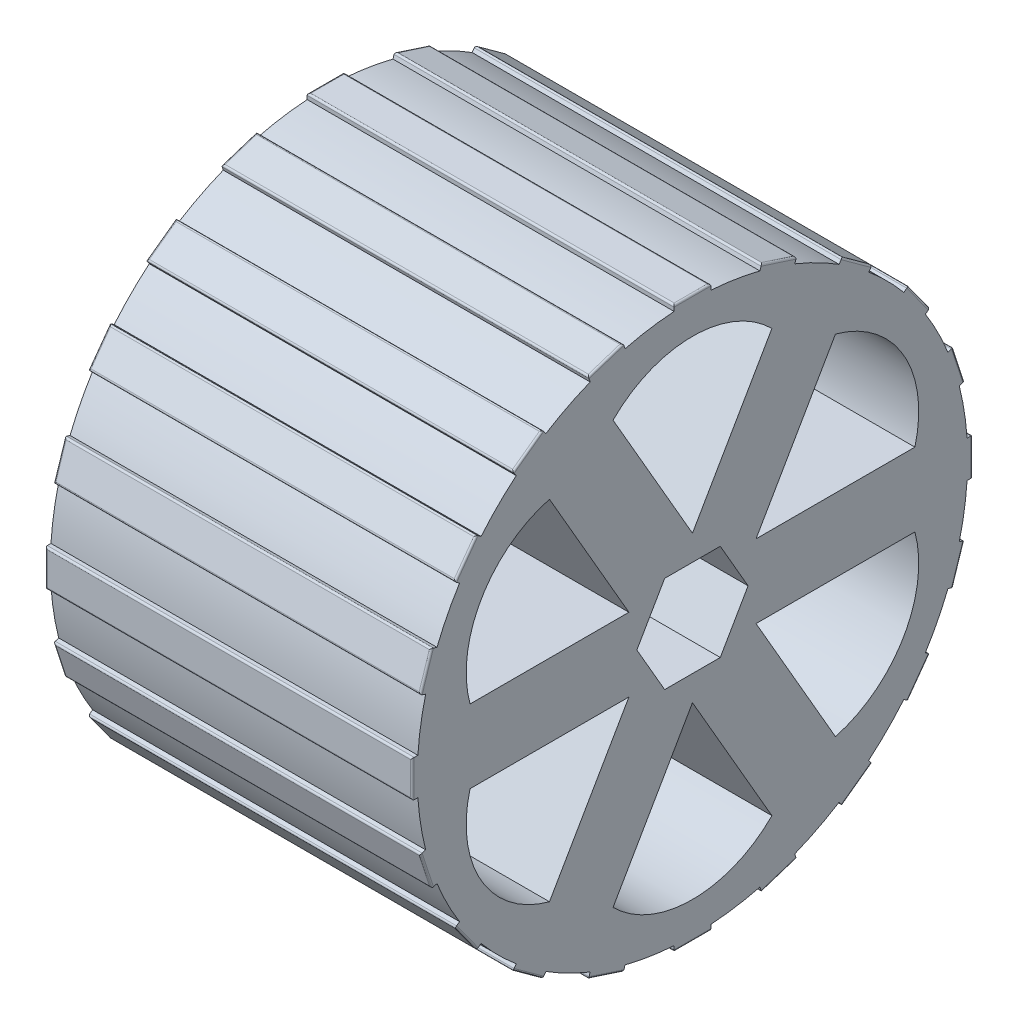
SolidWorks part; units mm, degrees
ref_plane "Front Plane" through (0, 0, 0) normal (0, 0, 1) x (1, 0, 0)
ref_plane "Top Plane" through (0, 0, 0) normal (0, 1, 0) x (1, 0, 0)
ref_plane "Right Plane" through (0, 0, 0) normal (1, 0, 0) x (0, 0, -1)
sketch "Sketch1" plane through (0, 0, 0) normal (1, 0, 0) x (0, 0, -1)
  line L2 (-2.54, 38.0152) -> (-2.54, 38.7772)
  line L3 (-2.54, 38.7772) -> (2.54, 38.7772)
  line L4 (2.54, 38.7772) -> (2.54, 38.0152)
  line L5 (14.3985, 36.0944) -> (14.163, 35.3697)
  line L6 (9.5671, 37.6642) -> (14.3985, 36.0944)
  line L7 (9.3317, 36.9395) -> (9.5671, 37.6642)
  line L8 (24.8476, 29.8785) -> (24.3997, 29.262)
  line L9 (20.7378, 32.8644) -> (24.8476, 29.8785)
  line L10 (20.2899, 32.2479) -> (20.7378, 32.8644)
  line L11 (32.8644, 20.7378) -> (32.2479, 20.2899)
  line L12 (29.8785, 24.8476) -> (32.8644, 20.7378)
  line L13 (29.262, 24.3997) -> (29.8785, 24.8476)
  line L14 (37.6642, 9.5671) -> (36.9395, 9.3317)
  line L15 (36.0944, 14.3985) -> (37.6642, 9.5671)
  line L16 (35.3697, 14.163) -> (36.0944, 14.3985)
  line L17 (38.7772, -2.54) -> (38.0152, -2.54)
  line L18 (38.7772, 2.54) -> (38.7772, -2.54)
  line L19 (38.0152, 2.54) -> (38.7772, 2.54)
  line L20 (36.0944, -14.3985) -> (35.3697, -14.163)
  line L21 (37.6642, -9.5671) -> (36.0944, -14.3985)
  line L22 (36.9395, -9.3317) -> (37.6642, -9.5671)
  line L23 (29.8785, -24.8476) -> (29.262, -24.3997)
  line L24 (32.8644, -20.7378) -> (29.8785, -24.8476)
  line L25 (32.2479, -20.2899) -> (32.8644, -20.7378)
  line L26 (20.7378, -32.8644) -> (20.2899, -32.2479)
  line L27 (24.8476, -29.8785) -> (20.7378, -32.8644)
  line L28 (24.3997, -29.262) -> (24.8476, -29.8785)
  line L29 (9.5671, -37.6642) -> (9.3317, -36.9395)
  line L30 (14.3985, -36.0944) -> (9.5671, -37.6642)
  line L31 (14.163, -35.3697) -> (14.3985, -36.0944)
  line L32 (-2.54, -38.7772) -> (-2.54, -38.0152)
  line L33 (2.54, -38.7772) -> (-2.54, -38.7772)
  line L34 (2.54, -38.0152) -> (2.54, -38.7772)
  line L35 (-14.3985, -36.0944) -> (-14.163, -35.3697)
  line L36 (-9.5671, -37.6642) -> (-14.3985, -36.0944)
  line L37 (-9.3317, -36.9395) -> (-9.5671, -37.6642)
  line L38 (-24.8476, -29.8785) -> (-24.3997, -29.262)
  line L39 (-20.7378, -32.8644) -> (-24.8476, -29.8785)
  line L40 (-20.2899, -32.2479) -> (-20.7378, -32.8644)
  line L41 (-32.8644, -20.7378) -> (-32.2479, -20.2899)
  line L42 (-29.8785, -24.8476) -> (-32.8644, -20.7378)
  line L43 (-29.262, -24.3997) -> (-29.8785, -24.8476)
  line L44 (-37.6642, -9.5671) -> (-36.9395, -9.3317)
  line L45 (-36.0944, -14.3985) -> (-37.6642, -9.5671)
  line L46 (-35.3697, -14.163) -> (-36.0944, -14.3985)
  line L47 (-38.7772, 2.54) -> (-38.0152, 2.54)
  line L48 (-38.7772, -2.54) -> (-38.7772, 2.54)
  line L49 (-38.0152, -2.54) -> (-38.7772, -2.54)
  line L50 (-36.0944, 14.3985) -> (-35.3697, 14.163)
  line L51 (-37.6642, 9.5671) -> (-36.0944, 14.3985)
  line L52 (-36.9395, 9.3317) -> (-37.6642, 9.5671)
  line L53 (-29.8785, 24.8476) -> (-29.262, 24.3997)
  line L54 (-32.8644, 20.7378) -> (-29.8785, 24.8476)
  line L55 (-32.2479, 20.2899) -> (-32.8644, 20.7378)
  line L56 (-20.7378, 32.8644) -> (-20.2899, 32.2479)
  line L57 (-24.8476, 29.8785) -> (-20.7378, 32.8644)
  line L58 (-24.3997, 29.262) -> (-24.8476, 29.8785)
  line L59 (-9.5671, 37.6642) -> (-9.3317, 36.9395)
  line L60 (-14.3985, 36.0944) -> (-9.5671, 37.6642)
  line L61 (-14.163, 35.3697) -> (-14.3985, 36.0944)
  arc A0 (-2.54, 38.0152) -> (-9.3317, 36.9395) centre (0, 0) ccw
  arc A1 (-14.163, 35.3697) -> (-20.2899, 32.2479) centre (0, 0) ccw
  arc A2 (-24.3997, 29.262) -> (-29.262, 24.3997) centre (0, 0) ccw
  arc A3 (-32.2479, 20.2899) -> (-35.3697, 14.163) centre (0, 0) ccw
  arc A4 (-36.9395, 9.3317) -> (-38.0152, 2.54) centre (0, 0) ccw
  arc A5 (-38.0152, -2.54) -> (-36.9395, -9.3317) centre (0, 0) ccw
  arc A6 (-35.3697, -14.163) -> (-32.2479, -20.2899) centre (0, 0) ccw
  arc A7 (-29.262, -24.3997) -> (-24.3997, -29.262) centre (0, 0) ccw
  arc A8 (-20.2899, -32.2479) -> (-14.163, -35.3697) centre (0, 0) ccw
  arc A9 (-9.3317, -36.9395) -> (-2.54, -38.0152) centre (0, 0) ccw
  arc A10 (2.54, -38.0152) -> (9.3317, -36.9395) centre (0, 0) ccw
  arc A11 (14.163, -35.3697) -> (20.2899, -32.2479) centre (0, 0) ccw
  arc A12 (24.3997, -29.262) -> (29.262, -24.3997) centre (0, 0) ccw
  arc A13 (32.2479, -20.2899) -> (35.3697, -14.163) centre (0, 0) ccw
  arc A14 (36.9395, -9.3317) -> (38.0152, -2.54) centre (0, 0) ccw
  arc A15 (38.0152, 2.54) -> (36.9395, 9.3317) centre (0, 0) ccw
  arc A16 (35.3697, 14.163) -> (32.2479, 20.2899) centre (0, 0) ccw
  arc A17 (29.262, 24.3997) -> (24.3997, 29.262) centre (0, 0) ccw
  arc A18 (20.2899, 32.2479) -> (14.163, 35.3697) centre (0, 0) ccw
  arc A19 (9.3317, 36.9395) -> (2.54, 38.0152) centre (0, 0) ccw
  point P85 (0, 0)
  dimension "D1" = 76.2
  dimension "D2" = 20
  dimension "D4" = 5.08
  dimension "D5" = 0.762
extrude "Boss-Extrude1" add sketch "Sketch1" along normal blind 50.8
fillet "Fillet1" radius 0.254 80 edges at (25.4, 14.3985, 36.0944) (50.8, 11.9828, 36.8793) (25.4, 9.5671, 37.6642) (0, 11.9828, 36.8793) (25.4, 2.54, 38.7772) (50.8, 0, 38.7772) (25.4, -2.54, 38.7772) (0, 0, 38.7772) (25.4, -9.5671, 37.6642) (50.8, -11.9828, 36.8793) (25.4, -14.3985, 36.0944) (0, -11.9828, 36.8793) (25.4, -20.7378, 32.8644) (50.8, -22.7927, 31.3714) (25.4, -24.8476, 29.8785) (0, -22.7927, 31.3714) (25.4, -29.8785, 24.8476) (50.8, -31.3714, 22.7927) (25.4, -32.8644, 20.7378) (0, -31.3714, 22.7927) (25.4, -36.0944, 14.3985) (50.8, -36.8793, 11.9828) (25.4, -37.6642, 9.5671) (0, -36.8793, 11.9828) (25.4, -38.7772, 2.54) (50.8, -38.7772, 0) (25.4, -38.7772, -2.54) (0, -38.7772, 0) (25.4, -37.6642, -9.5671) (50.8, -36.8793, -11.9828) (25.4, -36.0944, -14.3985) (0, -36.8793, -11.9828) (25.4, -32.8644, -20.7378) (50.8, -31.3714, -22.7927) (25.4, -29.8785, -24.8476) (0, -31.3714, -22.7927) (25.4, -24.8476, -29.8785) (50.8, -22.7927, -31.3714) (25.4, -20.7378, -32.8644) (0, -22.7927, -31.3714) (25.4, -14.3985, -36.0944) (50.8, -11.9828, -36.8793) (25.4, -9.5671, -37.6642) (0, -11.9828, -36.8793) (25.4, -2.54, -38.7772) (50.8, 0, -38.7772) (25.4, 2.54, -38.7772) (0, 0, -38.7772) (25.4, 9.5671, -37.6642) (50.8, 11.9828, -36.8793) (25.4, 14.3985, -36.0944) (0, 11.9828, -36.8793) (25.4, 20.7378, -32.8644) (50.8, 22.7927, -31.3714) (25.4, 24.8476, -29.8785) (0, 22.7927, -31.3714) (25.4, 29.8785, -24.8476) (50.8, 31.3714, -22.7927) (25.4, 32.8644, -20.7378) (0, 31.3714, -22.7927) (25.4, 36.0944, -14.3985) (50.8, 36.8793, -11.9828) (25.4, 37.6642, -9.5671) (0, 36.8793, -11.9828) (25.4, 38.7772, -2.54) (50.8, 38.7772, 0) (25.4, 38.7772, 2.54) (0, 38.7772, 0) (25.4, 37.6642, 9.5671) (50.8, 36.8793, 11.9828) (25.4, 36.0944, 14.3985) (0, 36.8793, 11.9828) (25.4, 32.8644, 20.7378) (50.8, 31.3714, 22.7927) (25.4, 29.8785, 24.8476) (0, 31.3714, 22.7927) (25.4, 24.8476, 29.8785) (50.8, 22.7927, 31.3714) (25.4, 20.7378, 32.8644) (0, 22.7927, 31.3714)
sketch "Sketch2" plane through (0, 0, 0) normal (-1, 0, 0) x (0, 0, 1)
  line L1 (7.699, 0) -> (3.8495, 6.6675)
  line L2 (3.8495, 6.6675) -> (-3.8495, 6.6675)
  line L3 (-3.8495, 6.6675) -> (-7.699, 0)
  line L4 (-7.699, 0) -> (-3.8495, -6.6675)
  line L5 (-3.8495, -6.6675) -> (3.8495, -6.6675)
  line L6 (3.8495, -6.6675) -> (7.699, 0)
  circle A0 centre (0, 0) radius 6.6675 construction
extrude "Cut-Extrude1" cut sketch "Sketch2" against normal blind 50.8
sketch "Sketch3" plane through (0, 0, 0) normal (-1, 0, 0) x (0, 0, 1)
  line L0 (19.7973, 24.13) -> (8.7988, 5.08)
  line L1 (0, 10.16) -> (10.9985, 29.21)
  line L3 (-10.9985, 29.21) -> (0, 10.16)
  line L4 (10.9985, 29.21) -> (0, 29.21) [skipped]
  line L5 (8.7988, 5.08) -> (30.7959, 5.08)
  line L6 (30.7959, -5.08) -> (8.7988, -5.08)
  line L7 (8.7988, -5.08) -> (19.7973, -24.13)
  line L8 (10.9985, -29.21) -> (0, -10.16)
  line L9 (0, -10.16) -> (-10.9985, -29.21)
  line L10 (-19.7973, -24.13) -> (-8.7988, -5.08)
  line L11 (-8.7988, -5.08) -> (-30.7959, -5.08)
  line L12 (-30.7959, 5.08) -> (-8.7988, 5.08)
  line L13 (-8.7988, 5.08) -> (-19.7973, 24.13)
  circle A0 centre (0, 22.86) radius 6.35 construction
  arc A1 (-10.9985, 29.21) -> (10.9985, 29.21) centre (0, 18.2115) cw
  arc A2 (19.7973, 24.13) -> (30.7959, 5.08) centre (15.7716, 9.1057) cw
  arc A3 (30.7959, -5.08) -> (19.7973, -24.13) centre (15.7716, -9.1057) cw
  arc A4 (10.9985, -29.21) -> (-10.9985, -29.21) centre (0, -18.2115) cw
  arc A5 (-19.7973, -24.13) -> (-30.7959, -5.08) centre (-15.7716, -9.1057) cw
  arc A6 (-30.7959, 5.08) -> (-19.7973, 24.13) centre (-15.7716, 9.1057) cw
  point P31 (0, 0)
  dimension "D2" = 12.7
  dimension "D1" = 22.86
  dimension "D3" = 6
extrude "Cut-Extrude2" cut sketch "Sketch3" against normal blind 50.8
